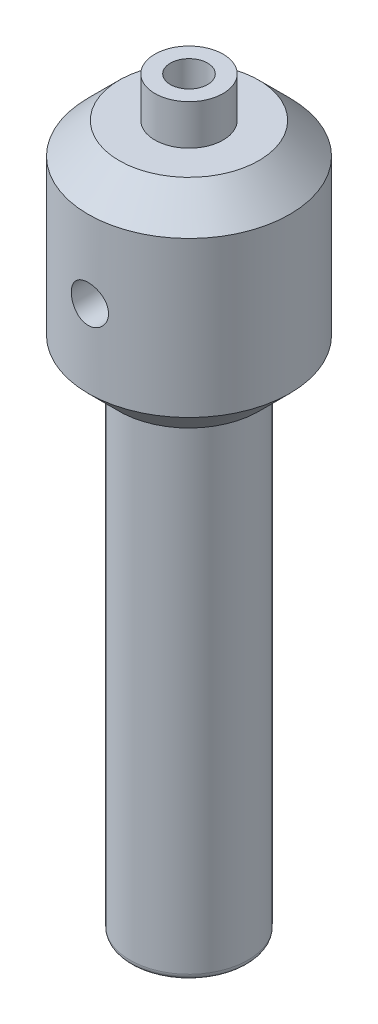
SolidWorks part; units mm, degrees
ref_plane "Front Plane" through (0, 0, 0) normal (0, 0, 1) x (1, 0, 0)
ref_plane "Top Plane" through (0, 0, 0) normal (0, 1, 0) x (1, 0, 0)
ref_plane "Right Plane" through (0, 0, 0) normal (1, 0, 0) x (0, 0, -1)
sketch "Sketch1" plane through (0, 0, 0) normal (0, 0, 1) x (1, 0, 0)
  line L6 (0, 0) -> (0, 240)
  line L7 (0, 240) -> (11, 240)
  line L8 (11, 240) -> (11, 227)
  line L9 (11, 227) -> (32.5, 227)
  line L10 (32.5, 227) -> (32.5, 157)
  line L11 (32.5, 157) -> (19, 157)
  line L12 (19, 157) -> (19, 0)
  line L13 (19, 0) -> (0, 0)
  dimension "D1" = 240
  dimension "D2" = 13
  dimension "D3" = 83
  dimension "D4" = 19
  dimension "D5" = 32.5
  dimension "D6" = 11
revolve "Revolve1" add sketch "Sketch1" angle 360 about L6
chamfer "Chamfer1" distance 10 angle 45 2 edges at (0, 157, -32.5) (0, 227, -32.5)
fillet "Fillet1" radius 2 1 edges at (0, 0, -19)
hole_wizard "Hole1" positions "Sketch2" profile "Sketch3" legacy
sketch "Sketch2" plane through (0, 240, 0) normal (0, 1, 0) x (1, 0, 0)
  point P0 (0, 0)
sketch "Sketch3" plane through (0, 240, 0) normal (1, 0, 0) x (0, 0, 1)
  line L0 (0, 0) -> (0, 23)
  line L1 (0, 23) -> (6, 23)
  line L2 (6, 23) -> (6, 0)
  line L3 (6, 0) -> (0, 0)
  line L4 (0, 110) -> (0, -10) construction
  dimension "Diameter" = 12
  dimension "Depth" = 23
sketch "Sketch4" plane through (0, 0, 0) normal (0, 0, 1) x (1, 0, 0)
  line L0 (11, 240) -> (-11, 240) construction
  circle A0 centre (0, 192) radius 6
  dimension "D1" = 12
  dimension "D2" = 48
extrude "Cut-Extrude1" cut sketch "Sketch4" against normal through all both and the other way through all
